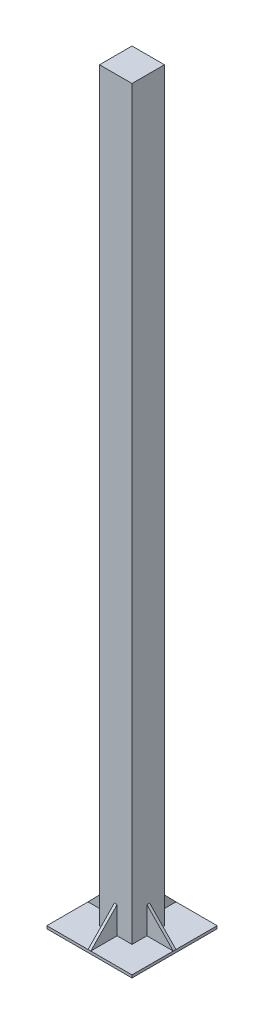
SolidWorks part; units mm, degrees
ref_plane "Alzado" through (0, 0, 0) normal (0, 0, 1) x (1, 0, 0)
ref_plane "Planta" through (0, 0, 0) normal (0, 1, 0) x (1, 0, 0)
ref_plane "Vista lateral" through (0, 0, 0) normal (1, 0, 0) x (0, 0, -1)
sketch "Croquis1" plane through (0, 0, 0) normal (0, 1, 0) x (1, 0, 0)
  line L1 (-200, -200) -> (200, -200)
  line L2 (-200, -200) -> (-200, 200)
  line L3 (-200, 200) -> (200, 200)
  line L4 (200, -200) -> (200, 200)
  line L5 (-200, -200) -> (200, 200) construction
  line L6 (-200, 200) -> (200, -200) construction
  point P0 (0, 0)
  dimension "D1" = 400
  dimension "D2" = 400
extrude "Saliente-Extruir1" add sketch "Croquis1" along normal blind 12.7
sketch "Croquis2" plane through (0, 12.7, 0) normal (0, 1, 0) x (1, 0, 0)
  line L0 (0, 200) -> (0, -200) construction
  line L1 (200, 200) -> (-200, 200) construction
  line L2 (-200, -200) -> (200, -200) construction
  line L4 (-76.2, -76.2) -> (76.2, -76.2)
  line L5 (-76.2, -76.2) -> (-76.2, 76.2)
  line L6 (-76.2, 76.2) -> (76.2, 76.2)
  line L7 (76.2, -76.2) -> (76.2, 76.2)
  line L8 (-76.2, -76.2) -> (76.2, 76.2) construction
  line L9 (-76.2, 76.2) -> (76.2, -76.2) construction
  point P6 (0, 0)
  dimension "D1" = 152.4
  dimension "D2" = 152.4
extrude "Saliente-Extruir2" add sketch "Croquis2" along normal blind 3500
sketch "Croquis3" plane through (0, 12.7, 0) normal (0, 1, 0) x (1, 0, 0)
  line L0 (200, 0) -> (76.2, 0) construction
  line L1 (200, -200) -> (200, 200) construction
  line L2 (76.2, -76.2) -> (76.2, 76.2) construction
  line L3 (0, -76.2) -> (0, 76.2) construction
  line L4 (200, 6.35) -> (76.2, 6.35)
  line L5 (200, 6.35) -> (200, -6.35)
  line L6 (200, -6.35) -> (76.2, -6.35)
  line L7 (76.2, 6.35) -> (76.2, -6.35)
  line L8 (200, 6.35) -> (76.2, -6.35) construction
  line L9 (200, -6.35) -> (76.2, 6.35) construction
  line L10 (-76.2, -76.2) -> (76.2, -76.2) construction
  line L11 (76.2, 76.2) -> (-76.2, 76.2) construction
  line L12 (-200, -6.35) -> (-76.2, 6.35) construction
  line L13 (-200, 6.35) -> (-76.2, -6.35) construction
  line L14 (-200, 0) -> (-76.2, 0) construction
  line L15 (-76.2, 6.35) -> (-76.2, -6.35)
  line L16 (-200, -6.35) -> (-76.2, -6.35)
  line L17 (-200, 6.35) -> (-200, -6.35)
  line L18 (-200, 6.35) -> (-76.2, 6.35)
  line L19 (76.2, 0) -> (-76.2, 0) construction
  line L20 (0, 76.2) -> (0, 200) construction
  line L21 (200, 200) -> (-200, 200) construction
  line L22 (6.35, -76.2) -> (-6.35, -200) construction
  line L23 (6.35, 200) -> (-6.35, 200)
  line L24 (6.35, 200) -> (6.35, 76.2)
  line L25 (6.35, 76.2) -> (-6.35, 76.2)
  line L26 (-6.35, 200) -> (-6.35, 76.2)
  line L27 (6.35, 200) -> (-6.35, 76.2) construction
  line L28 (6.35, 76.2) -> (-6.35, 200) construction
  line L29 (6.35, -200) -> (-6.35, -76.2) construction
  line L30 (0, -76.2) -> (0, -200) construction
  line L31 (-6.35, -200) -> (-6.35, -76.2)
  line L32 (6.35, -76.2) -> (-6.35, -76.2)
  line L33 (6.35, -200) -> (6.35, -76.2)
  line L34 (6.35, -200) -> (-6.35, -200)
  point P6 (138.1, 0)
  point P23 (-138.1, 0)
  point P24 (0, 138.1)
  point P37 (0, -138.1)
  dimension "D1" = 12.7
  dimension "D2" = 12.7
extrude "Saliente-Extruir3" add sketch "Croquis3" along normal blind 127
sketch "Croquis4" plane through (6.35, 0, 0) normal (1, 0, 0) x (0, 0, -1)
  line L0 (-200, 12.7) -> (-76.2, 139.7)
  line L1 (-76.2, 139.7) -> (-200, 139.7)
  line L2 (-200, 139.7) -> (-200, 12.7)
extrude "Cortar-Extruir1" cut sketch "Croquis4" against normal blind 13
sketch "Croquis5" plane through (0, 0, 6.35) normal (0, 0, 1) x (1, 0, 0)
  line L0 (-200, 12.7) -> (-76.2, 139.7)
  line L1 (-76.2, 139.7) -> (-200, 139.7)
  line L2 (-200, 139.7) -> (-200, 12.7)
extrude "Cortar-Extruir2" cut sketch "Croquis5" against normal blind 13
sketch "Croquis6" plane through (-6.35, 0, 0) normal (-1, 0, 0) x (0, 0, 1)
  line L0 (-76.2, 139.7) -> (-200, 12.7)
  line L1 (-200, 12.7) -> (-200, 139.7)
  line L2 (-200, 139.7) -> (-76.2, 139.7)
extrude "Cortar-Extruir3" cut sketch "Croquis6" against normal blind 13
sketch "Croquis7" plane through (0, 0, -6.35) normal (0, 0, -1) x (-1, 0, 0)
  line L0 (-76.2, 139.7) -> (-200, 12.7)
  line L1 (-200, 12.7) -> (-200, 139.7)
  line L2 (-200, 139.7) -> (-76.2, 139.7)
extrude "Cortar-Extruir4" cut sketch "Croquis7" against normal blind 13
